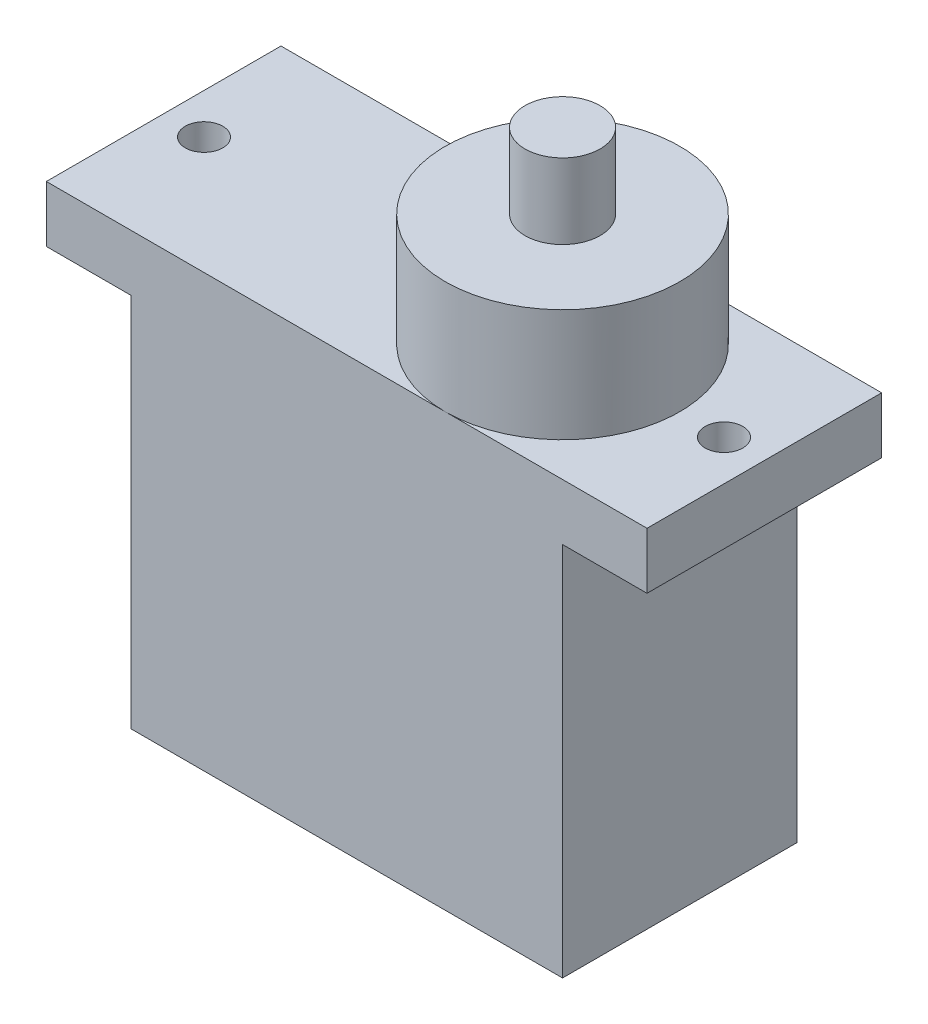
SolidWorks part; units mm, degrees
ref_plane "前视基准面" through (0, 0, 0) normal (0, 0, 1) x (1, 0, 0)
ref_plane "上视基准面" through (0, 0, 0) normal (0, 1, 0) x (1, 0, 0)
ref_plane "右视基准面" through (0, 0, 0) normal (1, 0, 0) x (0, 0, -1)
sketch "草图1" plane through (0, 0, 0) normal (0, 1, 0) x (1, 0, 0)
  line L1 (-11.5, 6.25) -> (11.5, 6.25)
  line L2 (-11.5, 6.25) -> (-11.5, -6.25)
  line L3 (-11.5, -6.25) -> (11.5, -6.25)
  line L4 (11.5, 6.25) -> (11.5, -6.25)
  line L5 (-11.5, 6.25) -> (11.5, -6.25) construction
  line L6 (-11.5, -6.25) -> (11.5, 6.25) construction
  point P0 (0, 0)
  dimension "D1" = 23
  dimension "D2" = 12.5
extrude "凸台-拉伸1" add sketch "草图1" along normal blind 20
ref_plane "基准面1" through (0, 20, 0) normal (0, 1, 0) x (1, 0, 0)
sketch "草图2" plane through (0, 20, 0) normal (0, 1, 0) x (1, 0, 0)
  line L0 (0, 0) -> (13.85, 0) construction
  line L1 (-16, 6.25) -> (16, 6.25)
  line L2 (-16, 6.25) -> (-16, -6.25)
  line L3 (-16, -6.25) -> (16, -6.25)
  line L4 (16, 6.25) -> (16, -6.25)
  line L5 (-16, 6.25) -> (16, -6.25) construction
  line L6 (-16, -6.25) -> (16, 6.25) construction
  line L7 (0, 6.25) -> (0, -6.25) construction
  circle A0 centre (13.85, 0) radius 1
  circle A1 centre (-13.85, 0) radius 1
  point P0 (0, 0)
  dimension "D3" = 2
  dimension "D1" = 32
  dimension "D2" = 13.85
extrude "凸台-拉伸2" add sketch "草图2" along normal blind 3
ref_plane "基准面2" through (0, 23, 0) normal (0, 1, 0) x (1, 0, 0)
sketch "草图4" plane through (0, 23, 0) normal (0, 1, 0) x (1, 0, 0)
  line L0 (11.5, -6.25) -> (11.5, 6.25) construction
  line L1 (-16, -6.25) -> (16, -6.25) construction
  line L2 (16, 6.25) -> (-16, 6.25) construction
  circle A0 centre (5.25, 0) radius 6.25
  point P6 (4.35, 0.9)
extrude "凸台-拉伸3" add sketch "草图4" along normal blind 6
ref_plane "基准面3" through (0, 29, 0) normal (0, 1, 0) x (1, 0, 0)
sketch "草图5" plane through (0, 29, 0) normal (0, 1, 0) x (1, 0, 0)
  circle A0 centre (5.25, 0) radius 2
  dimension "D1" = 4
extrude "凸台-拉伸4" add sketch "草图5" along normal blind 4
